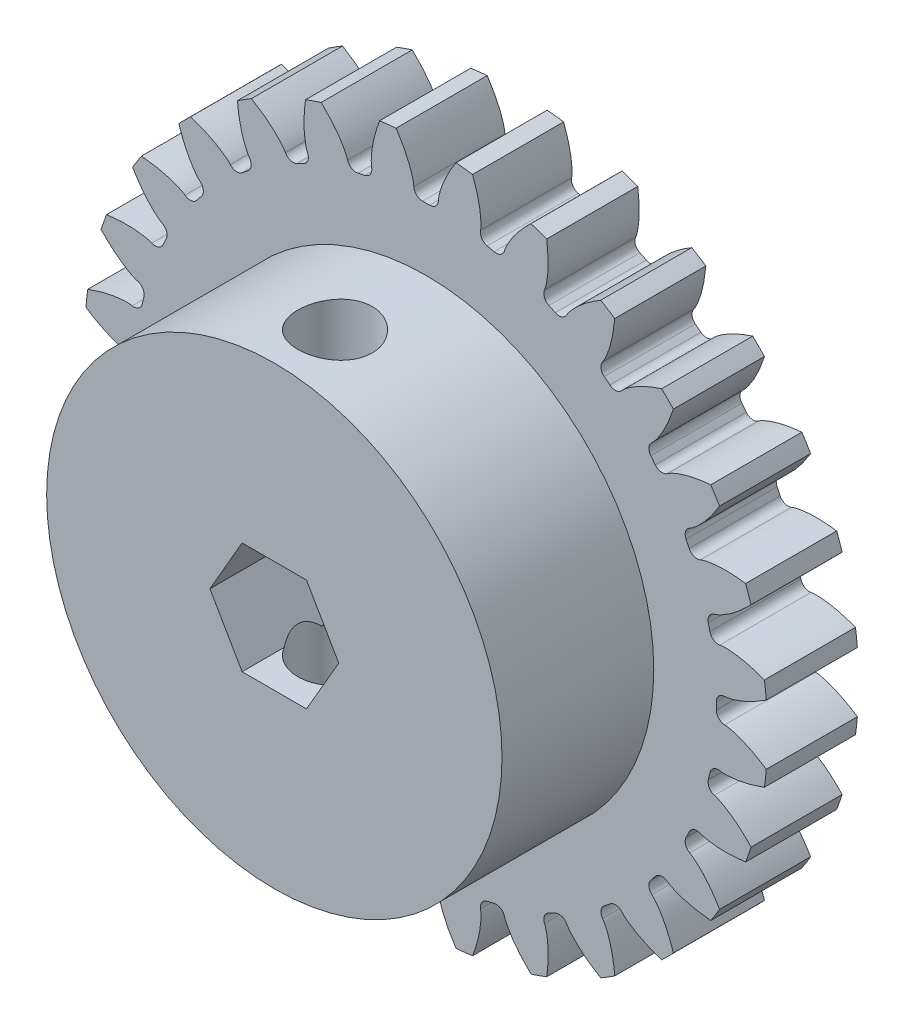
SolidWorks part; units mm, degrees
material "ABS"
ref_plane "前视基准面" through (0, 0, 0) normal (0, 0, 1) x (1, 0, 0)
ref_plane "上视基准面" through (0, 0, 0) normal (0, 1, 0) x (1, 0, 0)
ref_plane "右视基准面" through (0, 0, 0) normal (1, 0, 0) x (0, 0, -1)
ref_axis "Axis1" through (0, 0, -88.99) along (0, 0, 1)
sketch "草图1" plane through (0, 0, 0) normal (0, 0, 1) x (1, 0, 0)
  circle A0 centre (0, 0) radius 22.5
extrude "LaShenA" add sketch "草图1" along normal blind 6
sketch "SketchA" plane through (0, 0, 6) normal (0, 0, 1) x (1, 0, 0)
  line L0 (0, 0) -> (0, 22.5) construction
  arc A0 (0.2341, 19.1236) -> (-0.2341, 19.1236) centre (0, 0) ccw
  arc A1 (2.5188, 23.1604) -> (-2.5188, 23.1604) centre (0, 0) ccw
  arc A2 (-0.2341, 19.1236) -> (-0.8106, 19.669) centre (-0.2411, 19.6935) cw
  arc A3 (0.8106, 19.669) -> (0.2341, 19.1236) centre (0.2411, 19.6935) cw
  circle A4 centre (0, 0) radius 19.7335 construction
  circle A5 centre (0, 0) radius 22.5 construction
  circle A6 centre (0, 0) radius 19.125 construction
  circle A7 centre (0, 0) radius 21 construction
  spline S0 degree 3 poles (0.8106, 19.669) (0.8113, 19.6849) (0.8132, 19.7195) (0.8176, 19.7684) (0.8244, 19.8198) (0.8331, 19.875) (0.8453, 19.9423) (0.8618, 20.0214) (0.8831, 20.1122) (0.9098, 20.2145) (0.9425, 20.328) (0.9817, 20.4525) (1.0281, 20.5877) (1.0822, 20.7334) (1.1445, 20.8893) (1.2157, 21.0549) (1.2961, 21.2301) (1.3864, 21.4143) (1.4871, 21.6072) (1.5985, 21.8084) (1.7213, 22.0174) (1.8559, 22.2339) (2.0026, 22.4573) (2.2199, 22.7707) (2.3955, 23.0043) (2.5188, 23.1604) knots 0.12492 0.12492 0.12492 0.12492 0.135578 0.148024 0.157705 0.170153 0.185367 0.203347 0.224093 0.247605 0.273884 0.302929 0.334739 0.369316 0.406659 0.446769 0.489644 0.535286 0.583693 0.634867 0.688807 0.745514 0.804986 0.867224 1 1 1 1
  spline S1 degree 3 poles (-0.8106, 19.669) (-0.8113, 19.6849) (-0.8132, 19.7195) (-0.8176, 19.7684) (-0.8244, 19.8198) (-0.8331, 19.875) (-0.8453, 19.9423) (-0.8618, 20.0214) (-0.8831, 20.1122) (-0.9098, 20.2145) (-0.9425, 20.328) (-0.9817, 20.4525) (-1.0281, 20.5877) (-1.0822, 20.7334) (-1.1445, 20.8893) (-1.2157, 21.0549) (-1.2961, 21.2301) (-1.3864, 21.4143) (-1.4871, 21.6072) (-1.5985, 21.8084) (-1.7213, 22.0174) (-1.8559, 22.2339) (-2.0026, 22.4573) (-2.2199, 22.7707) (-2.3955, 23.0043) (-2.5188, 23.1604) knots 0.12492 0.12492 0.12492 0.12492 0.135578 0.148024 0.157705 0.170153 0.185367 0.203347 0.224093 0.247605 0.273884 0.302929 0.334739 0.369316 0.406659 0.446769 0.489644 0.535286 0.583693 0.634867 0.688807 0.745514 0.804986 0.867224 1 1 1 1
  dimension "D1" = 0.57
  dimension "Db" = 39.4671
  dimension "Da" = 45
  dimension "Df" = 38.25
  dimension "Dn" = 42
extrude "Cut-ExtrudeA" cut sketch "SketchA" against normal blind 6
pattern_circular "www.KYTool.cn" count 28 over 360 about axis through (0, 0, -88.99) along (0, 0, 1) of "Cut-ExtrudeA"
sketch "草图3" plane through (0, 0, 6) normal (0, 0, 1) x (1, 0, 0)
  line L1 (4.2435, 0) -> (2.1218, 3.675)
  line L2 (2.1218, 3.675) -> (-2.1218, 3.675)
  line L3 (-2.1218, 3.675) -> (-4.2435, 0)
  line L4 (-4.2435, 0) -> (-2.1218, -3.675)
  line L5 (-2.1218, -3.675) -> (2.1218, -3.675)
  line L6 (2.1218, -3.675) -> (4.2435, 0)
  circle A1 centre (0, 0) radius 15
  circle A2 centre (0, 0) radius 3.675 construction
  dimension "D2" = 30
  dimension "D1" = 7.35
extrude "凸台-拉伸2" add sketch "草图3" along normal blind 10
sketch "草图4" plane through (0, 0, 6) normal (0, 0, 1) x (1, 0, 0)
  line L6 (2.1218, -3.675) -> (4.2435, 0)
  line L7 (4.2435, 0) -> (2.1218, 3.675)
  line L8 (2.1218, 3.675) -> (-2.1218, 3.675)
  line L9 (-2.1218, 3.675) -> (-4.2435, 0)
  line L10 (-4.2435, 0) -> (-2.1218, -3.675)
  line L11 (-2.1218, -3.675) -> (2.1218, -3.675)
  line L12 (2.1218, -3.675) -> (4.2435, 0)
  line L13 (4.2435, 0) -> (2.1218, 3.675)
  line L14 (2.1218, 3.675) -> (-2.1218, 3.675)
  line L15 (-2.1218, 3.675) -> (-4.2435, 0)
  line L16 (-4.2435, 0) -> (-2.1218, -3.675)
  line L17 (-2.1218, -3.675) -> (2.1218, -3.675)
  dimension "D1" = 0
extrude "切除-拉伸2" cut sketch "草图4" against normal through all contours L12 L13 L14 L15 L16 L17
sketch "草图5" plane through (0, 3.675, 0) normal (0, -1, 0) x (1, 0, 0)
  line L0 (15, 16) -> (-15, 16) construction
  circle A0 centre (0, 12) radius 2.45
  dimension "D1" = 4.9
  dimension "D2" = 4
extrude "切除-拉伸3" cut sketch "草图5" against normal through all both and the other way through all
